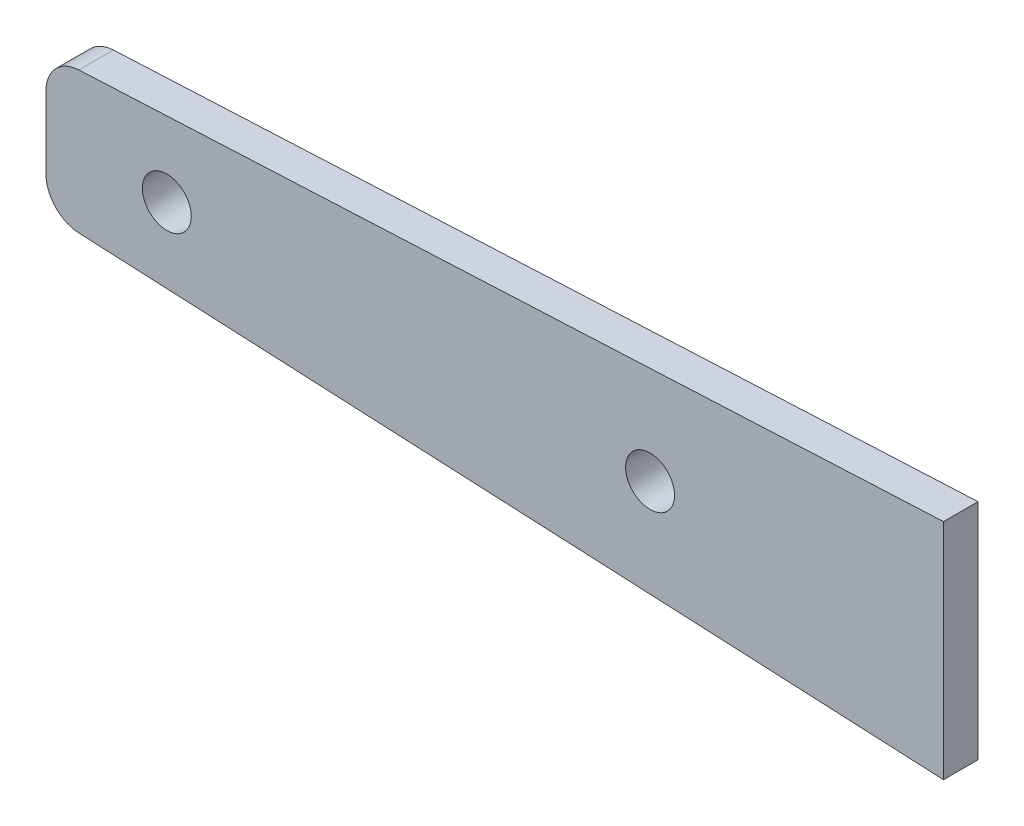
SolidWorks part; units mm, degrees
material "ASTM A36 Steel"
ref_plane "X-Y Datum" through (0, 0, 0) normal (0, 0, 1) x (1, 0, 0)
ref_plane "X-Z Datum" through (0, 0, 0) normal (0, 1, 0) x (1, 0, 0)
ref_plane "Y-Z Datum" through (0, 0, 0) normal (1, 0, 0) x (0, 0, -1)
sketch "Sketch1" plane through (0, 0, 0) normal (0, 0, 1) x (1, 0, 0)
  line L0 (-22.225, 0) -> (22.225, 0) construction
  line L1 (33.3375, 9.525) -> (33.3375, -9.525) construction
  line L6 (-33.3375, 9.525) -> (33.3375, 9.525) construction
  line L7 (-33.3375, 9.525) -> (-33.3375, -9.525) construction
  line L12 (-33.3375, -9.525) -> (33.3375, -9.525) construction
  line L13 (33.3375, 9.525) -> (33.3375, -9.525) construction
  line L14 (-33.3375, 9.525) -> (33.3375, -9.525) construction
  line L15 (-33.3375, -9.525) -> (33.3375, 9.525) construction
  line L16 (-33.3375, 6.35) -> (-33.3375, -6.35)
  line L17 (-33.3375, 6.35) -> (33.3375, 9.525)
  line L18 (-33.3375, -6.35) -> (33.3375, -9.525)
  line L19 (49.2125, 10.281) -> (49.2125, -10.281)
  line L21 (33.3375, 9.525) -> (33.3375, -9.525) construction
  line L24 (33.3375, 9.525) -> (49.2125, 10.281)
  line L25 (33.3375, -9.525) -> (49.2125, -10.281)
  circle A2 centre (-22.225, 0) radius 2 construction
  circle A3 centre (22.225, 0) radius 2 construction
  point P5 (52.3875, -10.0178)
  point P6 (0, 0)
  point P8 (0, 0)
  point P14 (33.3375, 0)
  point P16 (-33.3375, 0)
  point P19 (49.2125, 0)
  dimension "D1" = 4
  dimension "D2" = 19.05
  dimension "D3" = 66.675
  dimension "D4" = 44.45
  dimension "D5" = 12.7
  dimension "D6" = 15.875
extrude "Boss-Extrude1" add sketch "Sketch1" along normal blind 3.175
hole_wizard "M4 Clearance Hole2" positions "Sketch9" profile "Sketch8" hole size "M4" standard "ANSI Metric" end condition through all
sketch "Sketch9" plane through (0, 0, 3.175) normal (0, 0, 1) x (1, 0, 0)
  point P0 (-22.225, 0)
  point P3 (22.225, 0)
sketch "Sketch8" plane through (-22.225, 0, 3.175) normal (1, 0, 0) x (0, -1, 0)
  line L0 (0, 0) -> (0, 3.175)
  line L1 (0, 3.175) -> (2.25, 3.175)
  line L2 (2.25, 3.175) -> (2.25, 0)
  line L5 (2.25, 0) -> (0, 0)
  line L11 (0, -6.35) -> (0, 107.95) construction
  dimension "Thru Hole Dia." = 4.5
  dimension "Thru Hole Depth" = 3.175
fillet "Fillet1" radius 3.175 2 edges at (-33.3375, -6.35, 1.5875) (-33.3375, 6.35, 1.5875)
